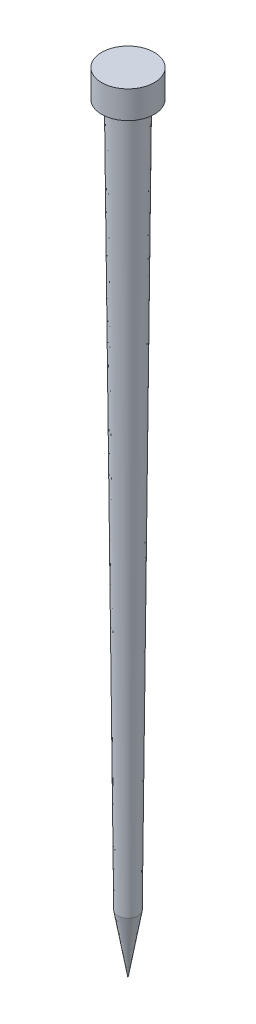
SolidWorks part; units mm, degrees
ref_plane "Front Plane" through (0, 0, 0) normal (0, 0, 1) x (1, 0, 0)
ref_plane "Top Plane" through (0, 0, 0) normal (0, 1, 0) x (1, 0, 0)
ref_plane "Right Plane" through (0, 0, 0) normal (1, 0, 0) x (0, 0, -1)
sketch "Sketch2" plane through (0, 0, 0) normal (0, 0, 1) x (1, 0, 0)
  line L0 (0, 14.7859) -> (0, -23.3141) construction
  line L1 (0, -23.3141) -> (0.3286, -21.4013)
  line L2 (0.3286, -21.4013) -> (0.4883, -20.4717)
  line L3 (0.4883, -20.4717) -> (0.8076, 13.4568)
  line L4 (1.27, 13.4568) -> (1.27, 14.7859)
  line L5 (1.27, 14.7859) -> (0, 14.7859)
  line L6 (0, 14.7859) -> (0, -23.3141)
  line L7 (0.8076, 13.4568) -> (1.27, 13.4568)
  dimension "D1" = 38.1
  dimension "D2" = 1.27
revolve "Revolve1" add sketch "Sketch2" angle 360 about L0
